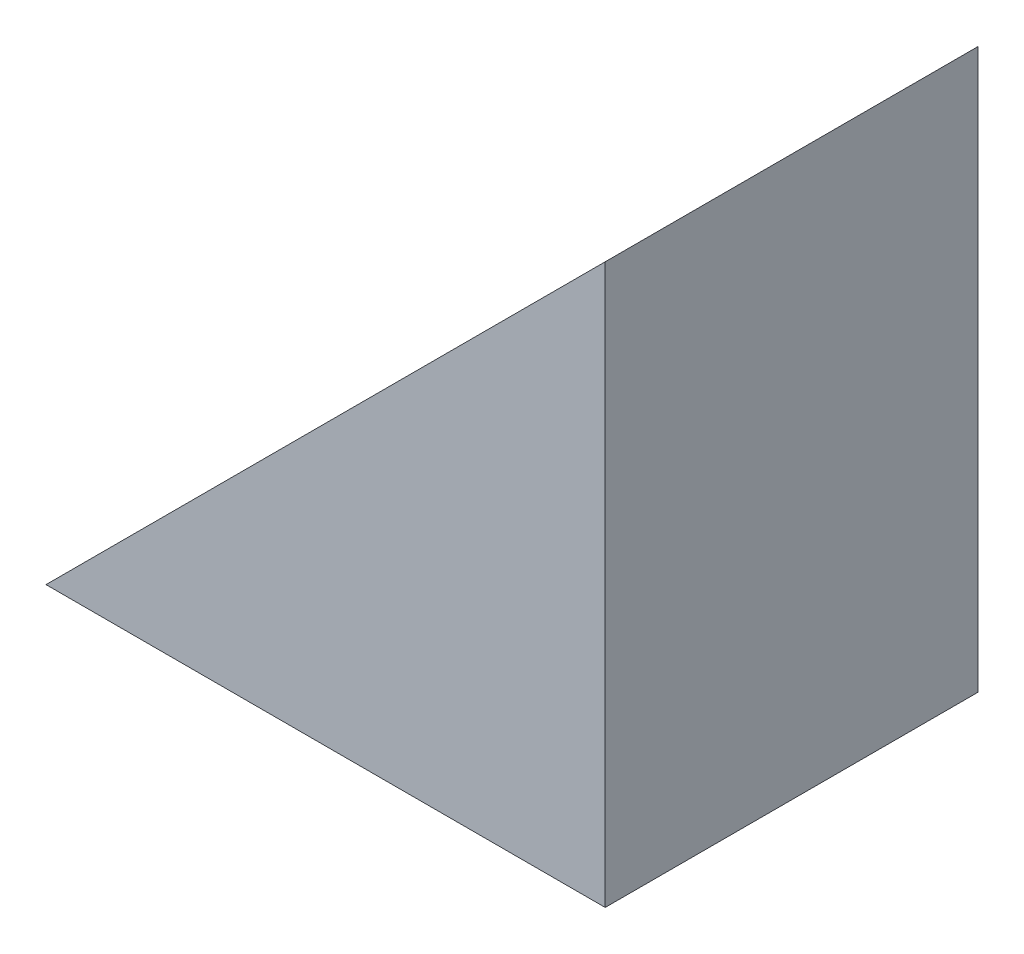
SolidWorks part; units mm, degrees
ref_plane "Plan de face" through (0, 0, 0) normal (0, 0, 1) x (1, 0, 0)
ref_plane "Plan de dessus" through (0, 0, 0) normal (0, 1, 0) x (1, 0, 0)
ref_plane "Plan de droite" through (0, 0, 0) normal (1, 0, 0) x (0, 0, -1)
sketch "Esquisse1" plane through (0, 0, 0) normal (0, 0, 1) x (1, 0, 0)
  line L0 (0, 0) -> (-76.2, 0)
  line L1 (-76.2, 0) -> (0, 76.2)
  line L2 (0, 304.8) -> (0, 0) construction
  line L3 (0, 76.2) -> (0, 0)
  dimension "D1" = 76.2
  dimension "D2" = 76.2
extrude "Boss.-Extru.1" add sketch "Esquisse1" against normal blind 50.8
